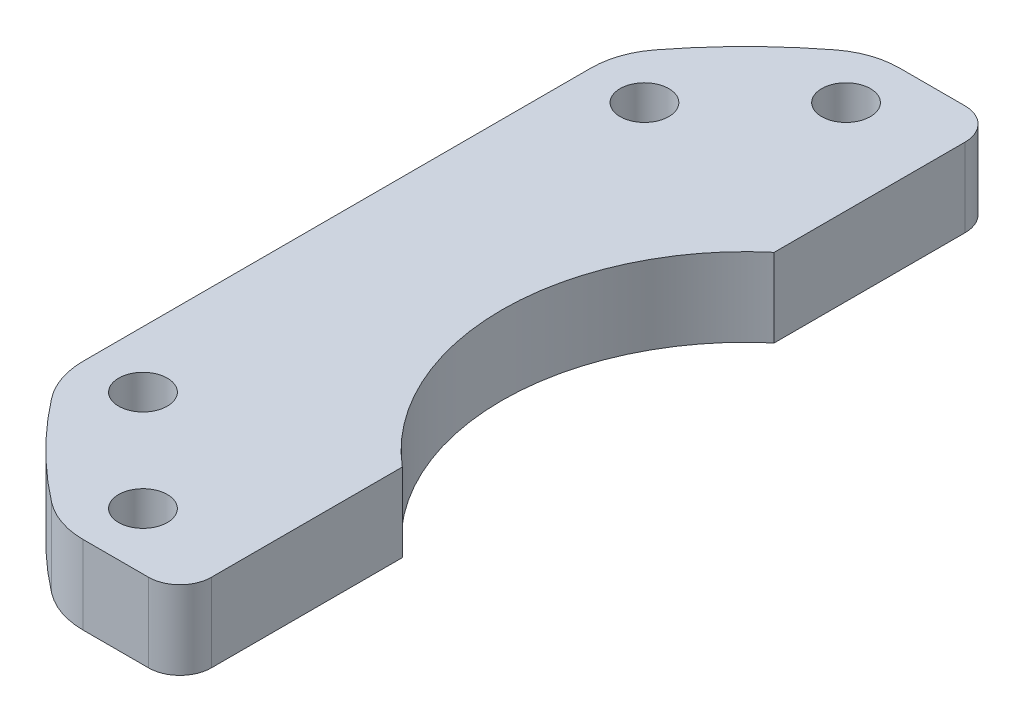
SolidWorks part; units mm, degrees
material "6061 合金"
ref_plane "前视基准面" through (0, 0, 0) normal (0, 0, 1) x (1, 0, 0)
ref_plane "上视基准面" through (0, 0, 0) normal (0, 1, 0) x (1, 0, 0)
ref_plane "右视基准面" through (0, 0, 0) normal (1, 0, 0) x (0, 0, -1)
sketch "草图1" plane through (0, 0, 0) normal (0, 1, 0) x (1, 0, 0)
  line L0 (-22.3882, 15.9693) -> (0, 0) construction
  line L1 (0, 0) -> (-27.5, 0) construction
  line L2 (0, 0) -> (-19.4454, 19.4454) construction
  line L3 (0, 0) -> (0, 27.5) construction
  line L4 (-17.7834, 26) -> (17.7834, 26)
  line L5 (26, 17.7834) -> (26, -17.7834)
  line L6 (17.7834, -26) -> (-17.7834, -26)
  line L7 (-26, -17.7834) -> (-26, 17.7834)
  circle A0 centre (0, 0) radius 15.5
  circle A1 centre (0, 0) radius 27.5 construction
  circle A2 centre (-22.3882, 15.9693) radius 1.55
  circle A3 centre (-15.9693, 22.3882) radius 1.55
  circle A4 centre (22.3882, 15.9693) radius 1.55
  circle A5 centre (15.9693, 22.3882) radius 1.55
  circle A6 centre (22.3882, -15.9693) radius 1.55
  circle A7 centre (15.9693, -22.3882) radius 1.55
  circle A8 centre (-22.3882, -15.9693) radius 1.55
  circle A9 centre (-15.9693, -22.3882) radius 1.55
  arc A10 (-17.7834, 26) -> (-26, 17.7834) centre (0, 0) ccw
  arc A11 (26, 17.7834) -> (17.7834, 26) centre (0, 0) ccw
  arc A12 (17.7834, -26) -> (26, -17.7834) centre (0, 0) ccw
  arc A13 (-26, -17.7834) -> (-17.7834, -26) centre (0, 0) ccw
  point P35 (0, 0)
  dimension "D1" = 31
  dimension "D2" = 55
  dimension "D3" = 3.1
  dimension "D6" = 63
  dimension "D4" = 35.5
  dimension "D5" = 45
  dimension "D7" = 26
  dimension "D8" = 4
extrude "凸台-拉伸1" add sketch "草图1" along normal blind 5
sketch "草图3" plane through (0, 5, 0) normal (0, 1, 0) x (1, 0, 0)
  line L0 (0, 0) -> (0, 26) construction
  line L1 (0, 0) -> (26, 0) construction
  line L2 (17.7834, 26) -> (-17.7834, 26) construction
  line L3 (-10, 41.4188) -> (34.7269, 41.4188)
  line L4 (-10, 41.4188) -> (-10, -30.362)
  line L5 (-10, -30.362) -> (34.7269, -30.362)
  line L6 (34.7269, 41.4188) -> (34.7269, -30.362)
  line L7 (26, -17.7834) -> (26, 17.7834) construction
  dimension "D1" = 10
extrude "切除-拉伸2" cut sketch "草图3" against normal blind 10
fillet "圆角1" radius 2 2 edges at (-10, 2.5, 26) (-10, 2.5, -26)
fillet "圆角2" radius 5 4 edges at (-17.7834, 2.5, 26) (-26, 2.5, 17.7834) (-26, 2.5, -17.7834) (-17.7834, 2.5, -26)
